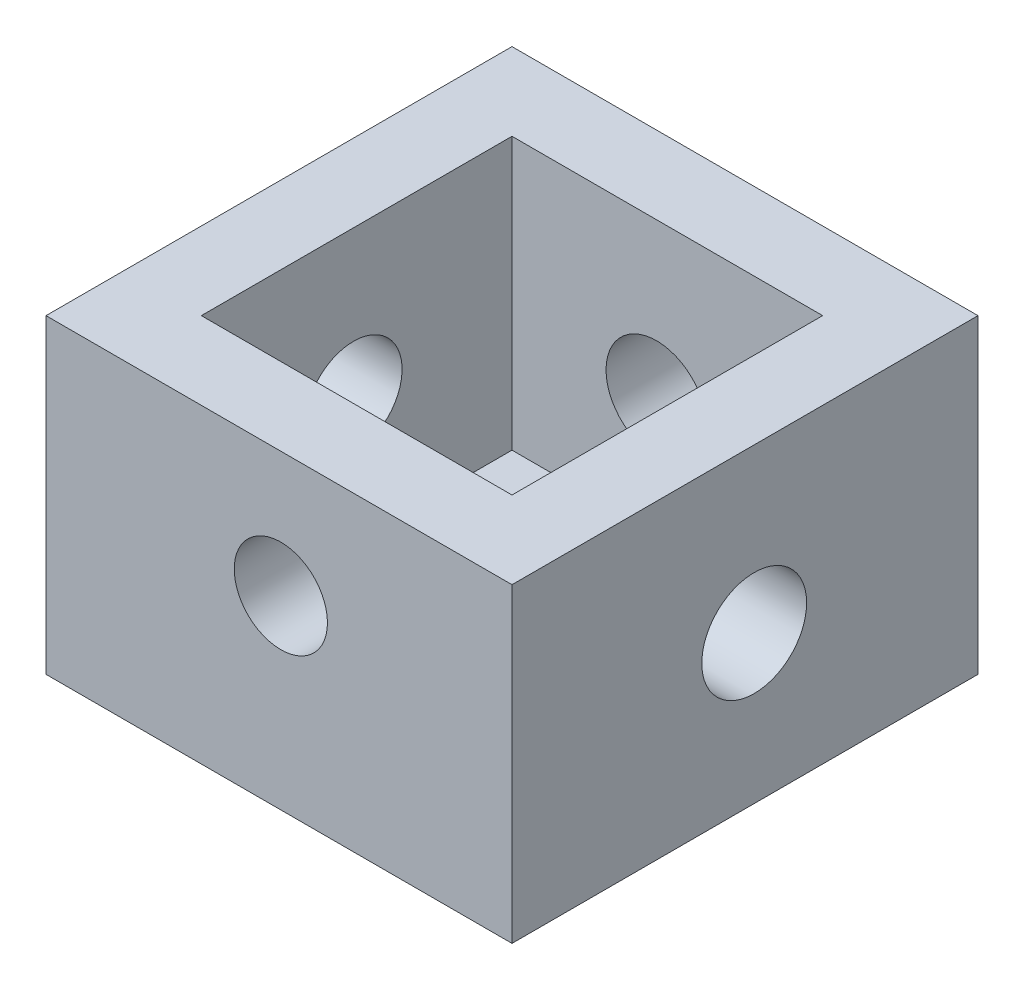
SolidWorks part; units mm, degrees
ref_plane "前基準面" through (0, 0, 0) normal (0, 0, 1) x (1, 0, 0)
ref_plane "上基準面" through (0, 0, 0) normal (0, 1, 0) x (1, 0, 0)
ref_plane "右基準面" through (0, 0, 0) normal (1, 0, 0) x (0, 0, -1)
sketch "草圖1" plane through (0, 0, 0) normal (0, 1, 0) x (1, 0, 0)
  line L1 (-47.6316, 77.2368) -> (12.3684, 77.2368)
  line L2 (-47.6316, 77.2368) -> (-47.6316, 17.2368)
  line L3 (-47.6316, 17.2368) -> (12.3684, 17.2368)
  line L4 (12.3684, 77.2368) -> (12.3684, 17.2368)
  line L5 (-47.6316, 77.2368) -> (12.3684, 17.2368) construction
  line L6 (-47.6316, 17.2368) -> (12.3684, 77.2368) construction
  point P0 (-17.6316, 47.2368)
  dimension "D1" = 60
extrude "填料-伸長2" add sketch "草圖1" along normal blind 40
sketch "草圖2" plane through (0, 40, 0) normal (0, 1, 0) x (1, 0, 0)
  line L0 (-17.6316, 77.2368) -> (-17.6316, 17.2368) construction
  line L1 (-37.6316, 67.2368) -> (2.3684, 67.2368)
  line L2 (-37.6316, 67.2368) -> (-37.6316, 27.2368)
  line L3 (-37.6316, 27.2368) -> (2.3684, 27.2368)
  line L4 (2.3684, 67.2368) -> (2.3684, 27.2368)
  line L5 (-37.6316, 67.2368) -> (2.3684, 27.2368) construction
  line L6 (-37.6316, 27.2368) -> (2.3684, 67.2368) construction
  line L7 (12.3684, 77.2368) -> (-47.6316, 77.2368) construction
  line L8 (-47.6316, 17.2368) -> (12.3684, 17.2368) construction
  point P0 (-17.6316, 47.2368)
  dimension "D1" = 40
extrude "除料-伸長1" cut sketch "草圖2" against normal blind 35
hole_wizard "Ø12.0 (12) 直徑孔1" positions "3D草圖3" profile "草圖5" hole size "Ø12.0" standard "ISO"
sketch3d "3D草圖3"
  point P0 (-17.3939, 23.8674, -17.2368)
sketch "草圖5" plane through (-17.3939, 23.8674, -17.2368) normal (1, 0, 0) x (0, -1, 0)
  line L0 (0, 0) -> (0, 10)
  line L1 (0, 10) -> (6, 10)
  line L2 (6, 10) -> (6, 0)
  line L5 (6, 0) -> (0, 0)
  line L11 (0, -6.35) -> (0, 107.95) construction
  dimension "貫穿孔直徑" = 12
  dimension "貫穿孔深度" = 10
hole_wizard "Ø13.5 (13.5) 直徑孔1" positions "3D草圖4" profile "草圖6" hole size "Ø13.5" standard "ISO"
sketch3d "3D草圖4"
  point P0 (12.3684, 19.0144, -48.4216)
sketch "草圖6" plane through (12.3684, 19.0144, -48.4216) normal (0, 1, 0) x (0, 0, -1)
  line L0 (0, 0) -> (0, 10)
  line L1 (0, 10) -> (6.75, 10)
  line L2 (6.75, 10) -> (6.75, 0)
  line L5 (6.75, 0) -> (0, 0)
  line L11 (0, -6.35) -> (0, 107.95) construction
  dimension "貫穿孔直徑" = 13.5
  dimension "貫穿孔深度" = 10
hole_wizard "Ø12.5 (12.5) 直徑孔1" positions "3D草圖5" profile "草圖7" hole size "Ø12.5" standard "ISO"
sketch3d "3D草圖5"
  point P0 (-47.6316, 21.0933, -46.8351)
sketch "草圖7" plane through (-47.6316, 21.0933, -46.8351) normal (0, 1, 0) x (0, 0, 1)
  line L0 (0, 0) -> (0, 10)
  line L1 (0, 10) -> (6.25, 10)
  line L2 (6.25, 10) -> (6.25, 0)
  line L5 (6.25, 0) -> (0, 0)
  line L11 (0, -6.35) -> (0, 107.95) construction
  dimension "貫穿孔直徑" = 12.5
  dimension "貫穿孔深度" = 10
hole_wizard "Ø13.0 (13) 直徑孔1" positions "3D草圖6" profile "草圖8" hole size "Ø13.0" standard "ISO"
sketch3d "3D草圖6"
  point P0 (-19.0227, 20.0118, -77.2368)
sketch "草圖8" plane through (-19.0227, 20.0118, -77.2368) normal (1, 0, 0) x (0, 1, 0)
  line L0 (0, 0) -> (0, 10)
  line L1 (0, 10) -> (6.5, 10)
  line L2 (6.5, 10) -> (6.5, 0)
  line L5 (6.5, 0) -> (0, 0)
  line L11 (0, -6.35) -> (0, 107.95) construction
  dimension "貫穿孔直徑" = 13
  dimension "貫穿孔深度" = 10
